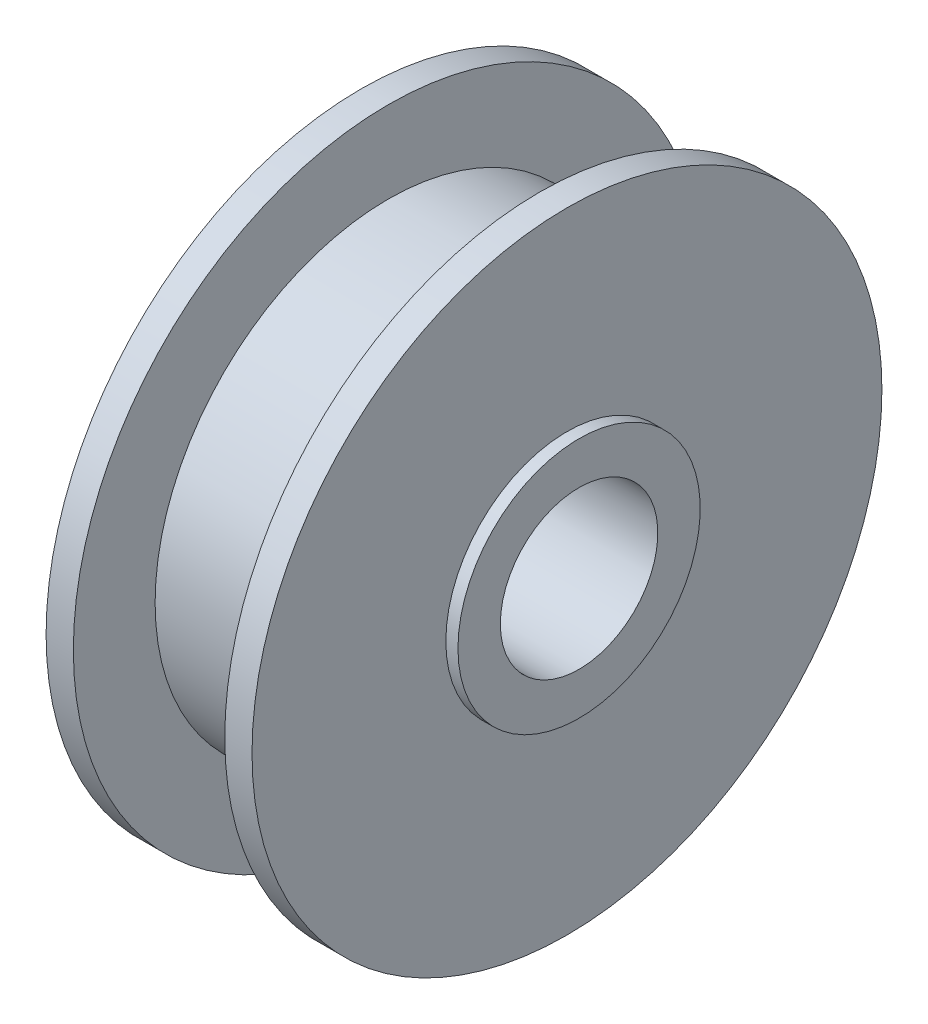
SolidWorks part; units mm, degrees
ref_plane "Front Plane" through (0, 0, 0) normal (0, 0, 1) x (1, 0, 0)
ref_plane "Top Plane" through (0, 0, 0) normal (0, 1, 0) x (1, 0, 0)
ref_plane "Right Plane" through (0, 0, 0) normal (1, 0, 0) x (0, 0, -1)
sketch "Sketch1" plane through (0, 0, 0) normal (0, 0, 1) x (1, 0, 0)
  line L0 (-1.9, 1.3) -> (-1.9, 2)
  line L1 (-1.9, 2) -> (-1.7, 2)
  line L2 (-1.7, 2) -> (-1.7, 5.2)
  line L3 (-1.7, 5.2) -> (-1.25, 5.2)
  line L4 (-1.25, 5.2) -> (-1.25, 3.85)
  line L5 (-1.25, 3.85) -> (1.25, 3.85)
  line L6 (1.25, 3.85) -> (1.25, 5.2)
  line L7 (1.25, 5.2) -> (1.7, 5.2)
  line L8 (1.7, 5.2) -> (1.7, 2)
  line L9 (1.7, 2) -> (1.9, 2)
  line L10 (1.9, 2) -> (1.9, 1.3)
  line L11 (1.9, 1.3) -> (-1.9, 1.3)
  line L12 (-1.9, 0) -> (1.9, 0) construction
  dimension "D1" = 2.5
  dimension "D2" = 3.8
  dimension "D3" = 0.45
  dimension "D4" = 0.2
  dimension "D5" = 1.3
  dimension "D6" = 2
  dimension "D7" = 5.2
  dimension "D8" = 3.85
revolve "Revolve1" add sketch "Sketch1" angle 360 about L12
